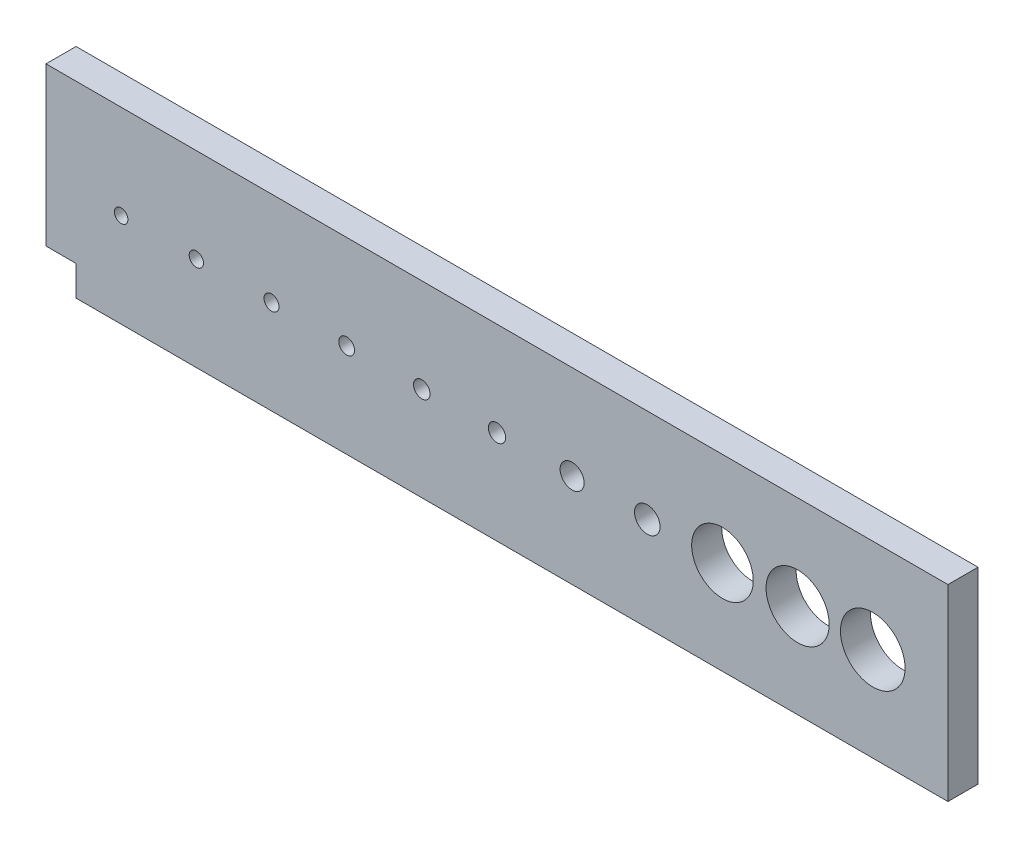
SolidWorks part; units mm, degrees
ref_plane "Front Plane" through (0, 0, 0) normal (0, 0, 1) x (1, 0, 0)
ref_plane "Top Plane" through (0, 0, 0) normal (0, 1, 0) x (1, 0, 0)
ref_plane "Right Plane" through (0, 0, 0) normal (1, 0, 0) x (0, 0, -1)
sketch "Sketch1" plane through (0, 0, 0) normal (0, 0, 1) x (1, 0, 0)
  line L1 (-60, -12.5) -> (60, -12.5)
  line L2 (-60, -12.5) -> (-60, 12.5)
  line L3 (-60, 12.5) -> (60, 12.5)
  line L4 (60, -12.5) -> (60, 12.5)
extrude "Coupon_120x25" add sketch "Sketch1" along normal blind 4 from offset 0
sketch "Sketch2" plane through (0, 0, 0) normal (0, 0, 1) x (1, 0, 0)
  circle A0 centre (-50, 0) radius 0.9
extrude "Diameter_1p8" cut sketch "Sketch2" along normal blind 4.2 from offset 0.1
sketch "Sketch3" plane through (0, 0, 0) normal (0, 0, 1) x (1, 0, 0)
  circle A0 centre (-40, 0) radius 0.95
extrude "Diameter_1p9" cut sketch "Sketch3" along normal blind 4.2 from offset 0.1
sketch "Sketch4" plane through (0, 0, 0) normal (0, 0, 1) x (1, 0, 0)
  circle A0 centre (-30, 0) radius 1
extrude "Diameter_2" cut sketch "Sketch4" along normal blind 4.2 from offset 0.1
sketch "Sketch5" plane through (0, 0, 0) normal (0, 0, 1) x (1, 0, 0)
  circle A0 centre (-20, 0) radius 1.05
extrude "Diameter_2p1" cut sketch "Sketch5" along normal blind 4.2 from offset 0.1
sketch "Sketch6" plane through (0, 0, 0) normal (0, 0, 1) x (1, 0, 0)
  circle A0 centre (-10, 0) radius 1.1
extrude "Diameter_2p2" cut sketch "Sketch6" along normal blind 4.2 from offset 0.1
sketch "Sketch7" plane through (0, 0, 0) normal (0, 0, 1) x (1, 0, 0)
  circle A0 centre (0, 0) radius 1.15
extrude "Diameter_2p3" cut sketch "Sketch7" along normal blind 4.2 from offset 0.1
sketch "Sketch8" plane through (0, 0, 0) normal (0, 0, 1) x (1, 0, 0)
  circle A0 centre (10, 0) radius 1.6
extrude "Diameter_3p2" cut sketch "Sketch8" along normal blind 4.2 from offset 0.1
sketch "Sketch9" plane through (0, 0, 0) normal (0, 0, 1) x (1, 0, 0)
  circle A0 centre (20, 0) radius 1.7
extrude "Diameter_3p4" cut sketch "Sketch9" along normal blind 4.2 from offset 0.1
sketch "Sketch10" plane through (0, 0, 0) normal (0, 0, 1) x (1, 0, 0)
  circle A0 centre (30, 0) radius 4.1
extrude "Diameter_8p2" cut sketch "Sketch10" along normal blind 4.2 from offset 0.1
sketch "Sketch11" plane through (0, 0, 0) normal (0, 0, 1) x (1, 0, 0)
  circle A0 centre (40, 0) radius 4.2
extrude "Diameter_8p4" cut sketch "Sketch11" along normal blind 4.2 from offset 0.1
sketch "Sketch12" plane through (0, 0, 0) normal (0, 0, 1) x (1, 0, 0)
  circle A0 centre (50, 0) radius 4.3
extrude "Diameter_8p6" cut sketch "Sketch12" along normal blind 4.2 from offset 0.1
sketch "Sketch13" plane through (0, 0, 0) normal (0, 0, 1) x (1, 0, 0)
  line L1 (-60, -12.5) -> (-56, -12.5)
  line L2 (-60, -12.5) -> (-60, -8.5)
  line L3 (-60, -8.5) -> (-56, -8.5)
  line L4 (-56, -12.5) -> (-56, -8.5)
extrude "Orientation_Notch" cut sketch "Sketch13" along normal blind 4.2 from offset 0.1
